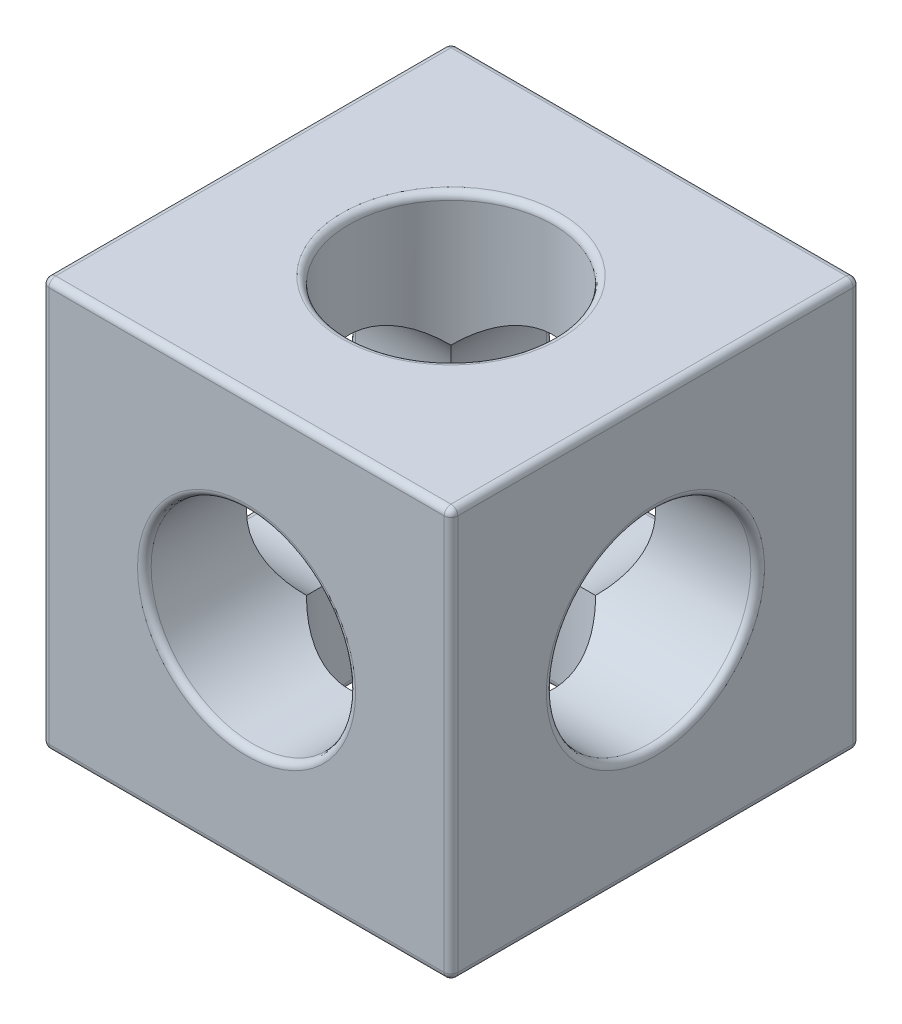
SolidWorks part; units mm, degrees
ref_plane "Front Plane" through (0, 0, 0) normal (0, 0, 1) x (1, 0, 0)
ref_plane "Top Plane" through (0, 0, 0) normal (0, 1, 0) x (1, 0, 0)
ref_plane "Right Plane" through (0, 0, 0) normal (1, 0, 0) x (0, 0, -1)
sketch "Sketch2" plane through (0, 0, 0) normal (0, 0, 1) x (1, 0, 0)
  line L1 (0, 0) -> (76.2, 0)
  line L2 (0, 0) -> (0, 76.2)
  line L3 (0, 76.2) -> (76.2, 76.2)
  line L4 (76.2, 0) -> (76.2, 76.2)
  point P5 (0, 0)
  dimension "D1" = 76.2
  dimension "D2" = 76.2
extrude "Boss-Extrude2" add sketch "Sketch2" along normal blind 76.2
sketch "Sketch3" plane through (0, 76.2, 0) normal (0, 1, 0) x (1, 0, 0)
  line L0 (76.2, 0) -> (0, 0) construction
  line L1 (0, -76.2) -> (0, 0) construction
  circle A0 centre (38.1, -38.1) radius 19.05
  point P2 (112.6407, -38.8381)
  point P3 (38.1, -38.1)
  point P6 (0, 0)
  point P9 (0, 0)
  dimension "D3" = 38.1
  dimension "D1" = 38.1
  dimension "D2" = 38.1
extrude "Cut-Extrude1" cut sketch "Sketch3" against normal blind 76.2
sketch "Sketch4" plane through (76.2, 0, 0) normal (1, 0, 0) x (0, 0, -1)
  line L0 (-76.2, 0) -> (0, 0) construction
  line L1 (-76.2, 0) -> (-76.2, 76.2) construction
  circle A0 centre (-38.1, 38.1) radius 19.05
  dimension "D3" = 38.1
  dimension "D1" = 38.1
  dimension "D2" = 38.1
extrude "Cut-Extrude2" cut sketch "Sketch4" against normal through all
sketch "Sketch5" plane through (0, 0, 0) normal (0, 0, -1) x (-1, 0, 0)
  line L0 (0, 76.2) -> (0, 0) construction
  line L2 (-76.2, 76.2) -> (0, 76.2) construction
  circle A0 centre (-38.1, 38.1) radius 19.05
  point P4 (0, 0)
  point P6 (-39.013, 44.1537)
  dimension "D3" = 38.1
  dimension "D1" = 38.1
  dimension "D2" = 38.1
extrude "Cut-Extrude3" cut sketch "Sketch5" against normal through all contours A0
fillet "Fillet2" radius 1.27 18 edges at (19.05, 38.1, 0) (0, 38.1, 0) (0, 57.15, 38.1) (0, 0, 38.1) (38.1, 0, 0) (38.1, 0, 57.15) (76.2, 0, 38.1) (76.2, 38.1, 0) (76.2, 57.15, 38.1) (76.2, 38.1, 76.2) (38.1, 0, 76.2) (0, 38.1, 76.2) (19.05, 38.1, 76.2) (76.2, 76.2, 38.1) (38.1, 76.2, 76.2) (0, 76.2, 38.1) (38.1, 76.2, 0) (38.1, 76.2, 57.15)
